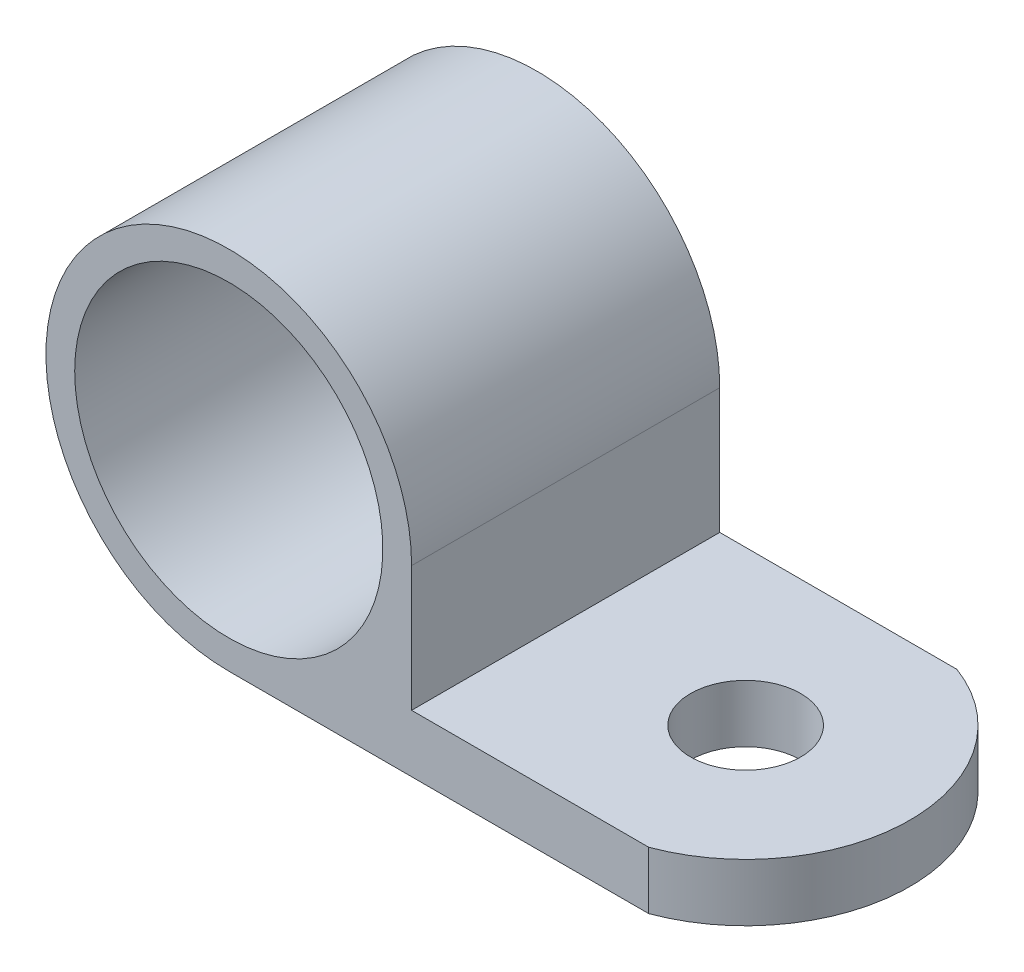
SolidWorks part; units mm, degrees
material "ASTM A36 Steel"
ref_plane "Front Plane" through (0, 0, 0) normal (0, 0, 1) x (1, 0, 0)
ref_plane "Top Plane" through (0, 0, 0) normal (0, 1, 0) x (1, 0, 0)
ref_plane "Right Plane" through (0, 0, 0) normal (1, 0, 0) x (0, 0, -1)
sketch "Sketch1" plane through (0, 0, 0) normal (0, 0, 1) x (1, 0, 0)
  line L0 (6.35, 0) -> (-11.2141, 0)
  line L1 (-5.5626, 5.6515) -> (-5.5626, 1.778)
  line L2 (-5.5626, 1.778) -> (6.35, 1.778)
  line L3 (6.35, 1.778) -> (6.35, 0)
  arc A0 (-11.2141, 0) -> (-5.5626, 5.6515) centre (-11.2141, 5.6515) cw
  circle A1 centre (-11.2141, 5.6515) radius 4.7625
  circle A2 centre (0, 1.778) radius 4.7625 construction
  dimension "D1" = 9.525
  dimension "D2" = 0.889
  dimension "D4" = 9.525
  dimension "D3" = 1.778
  dimension "D5" = 6.35
  dimension "D6" = 5.5626
extrude "Boss-Extrude1" add sketch "Sketch1" along normal mid plane 9.525
sketch "Sketch2" plane through (0, 0, 0) normal (0, 1, 0) x (1, 0, 0)
  line L0 (0, -5.08) -> (0, -11.8207)
  line L1 (0, -11.8207) -> (11.3811, -11.8207)
  line L2 (11.3811, -11.8207) -> (11.3811, 11.8207)
  line L3 (11.3811, 11.8207) -> (0, 11.8207)
  line L4 (0, 11.8207) -> (0, 5.08)
  circle A0 centre (0, 0) radius 1.7018
  arc A1 (0, -5.08) -> (0, 5.08) centre (0, 0) ccw
  dimension "D1" = 5.08
  dimension "D2" = 3.4036
extrude "Cut-Extrude1" cut sketch "Sketch2" along normal through all
